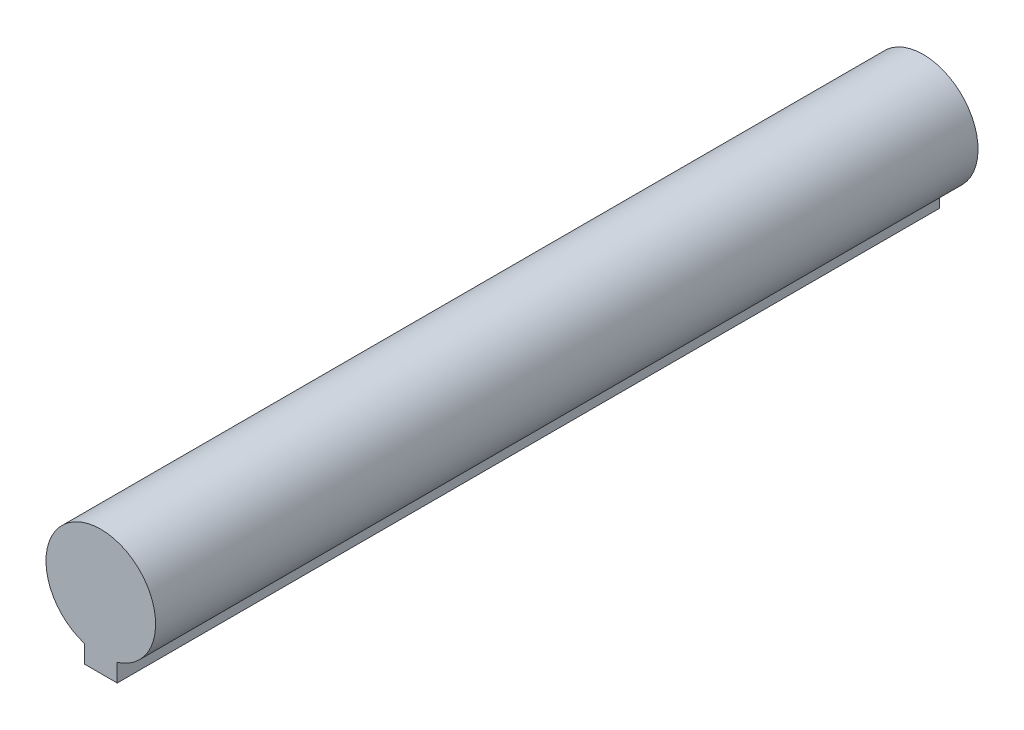
SolidWorks part; units mm, degrees
ref_plane "Front Plane" through (0, 0, 0) normal (0, 0, 1) x (1, 0, 0)
ref_plane "Top Plane" through (0, 0, 0) normal (0, 1, 0) x (1, 0, 0)
ref_plane "Right Plane" through (0, 0, 0) normal (1, 0, 0) x (0, 0, -1)
sketch "Sketch1" plane through (0, 0, 0) normal (0, 0, 1) x (1, 0, 0)
  line L3 (-3, -12.7994) -> (3, -12.7994)
  line L4 (3, -12.7994) -> (3, -9.5394)
  line L5 (-3, -12.7994) -> (-3, -9.5394)
  arc A1 (3, -9.5394) -> (-3, -9.5394) centre (0, 0) ccw
  dimension "D3" = 20
  dimension "D5" = 3.26
  dimension "D6" = 6
  dimension "D7" = 3.26
extrude "Boss-Extrude1" add sketch "Sketch1" along normal blind 150
